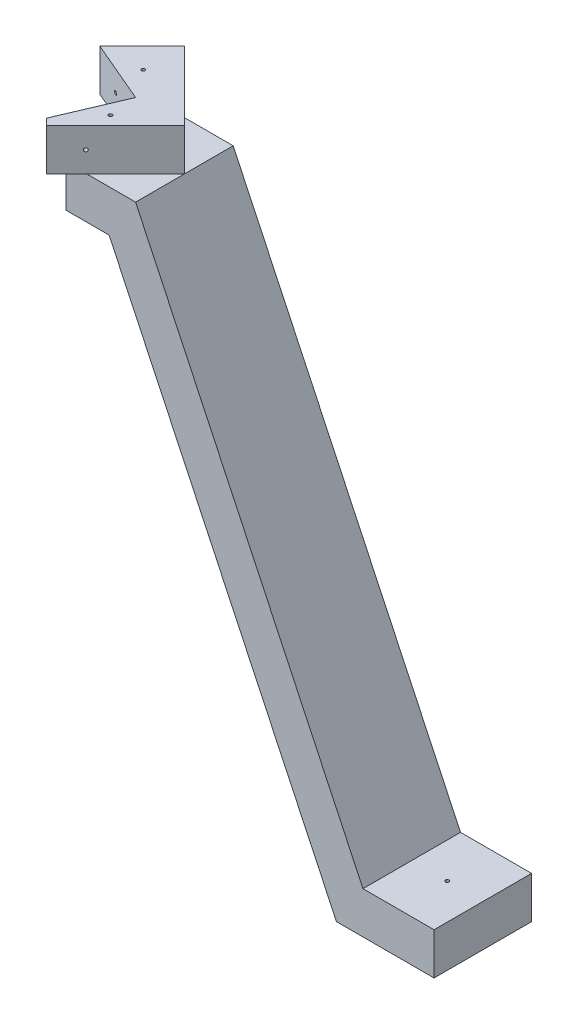
SolidWorks part; units mm, degrees
ref_plane "Frontal Plane" through (0, 0, 0) normal (0, 0, 1) x (1, 0, 0)
ref_plane "Horizontal Plane" through (0, 0, 0) normal (0, 1, 0) x (1, 0, 0)
ref_plane "Profile Plane" through (0, 0, 0) normal (1, 0, 0) x (0, 0, -1)
sketch "Sketch1" plane through (0, 0, 0) normal (0, 0, 1) x (1, 0, 0)
  line L0 (0, 0) -> (-207.1562, 438.15)
  line L2 (-183.0259, 476.25) -> (24.1302, 38.1)
  line L3 (24.1302, 38.1) -> (88.9, 38.1)
  line L4 (88.9, 38.1) -> (88.9, 0)
  line L5 (88.9, 0) -> (0, 0)
  line L6 (-183.0259, 476.25) -> (-271.9259, 476.25)
  line L7 (-271.9259, 476.25) -> (-271.9259, 438.15)
  line L8 (-271.9259, 438.15) -> (-207.1562, 438.15)
  point P7 (-227.4759, 476.25)
  point P9 (56.5151, 38.1)
  dimension "D1" = 38.1
  dimension "D2" = 88.9
  dimension "D3" = 283.991
  dimension "D4" = 438.15
  dimension "D5" = 88.9
  dimension "D6" = 38.1
extrude "Boss-Extrude1" add sketch "Sketch1" along normal mid plane 88.9
hole_wizard "1/8 (0.125) Diameter Hole1" positions "3DSketch1" profile "Sketch3" hole size "1/8" standard "ANSI Inch" end condition through all
sketch3d "3DSketch1"
  line L0 (88.9, 38.1, -44.45) -> (24.1302, 38.1, -44.45) construction
  line L2 (56.5151, 38.1, -44.45) -> (56.5151, 38.1, 44.45) construction
  line L3 (88.9, 38.1, 44.45) -> (24.1302, 38.1, 44.45) construction
  point P0 (56.5151, 38.1, 0)
  dimension "D1" = 44.45
sketch "Sketch3" plane through (56.5151, 38.1, 0) normal (1, 0, 0) x (0, 0, 1)
  line L0 (0, 0) -> (0, 38.1)
  line L1 (0, 38.1) -> (1.5875, 38.1)
  line L2 (1.5875, 38.1) -> (1.5875, 0)
  line L5 (1.5875, 0) -> (0, 0)
  line L11 (0, -6.35) -> (0, 107.95) construction
  dimension "Thru Hole Dia." = 3.175
  dimension "Thru Hole Depth" = 38.1
sketch "Sketch4" plane through (0, 476.25, 0) normal (0, 1, 0) x (1, 0, 0)
  line L0 (-245.8877, 62.8618) -> (-183.0259, 0)
  line L1 (-183.0259, 0) -> (-245.8877, -62.8618)
  line L3 (-245.8877, -62.8618) -> (-308.7495, 0)
  line L4 (-308.7495, 0) -> (-245.8877, 62.8618)
  line L7 (-183.0259, 44.45) -> (-271.9259, 44.45) construction
  line L8 (-271.9259, -44.45) -> (-271.9259, 44.45) construction
  dimension "D1" = 90
  dimension "D3" = 88.9
  dimension "D4" = 44.45
  dimension "D5" = 88.9
extrude "Boss-Extrude2" add sketch "Sketch4" along normal blind 38.1
sketch "Sketch6" plane through (0, 438.15, 0) normal (0, -1, 0) x (1, 0, 0)
  line L0 (-308.7495, 190.3683) -> (-227.4759, 0)
  line L1 (-227.4759, 0) -> (-308.7495, -34.698)
  line L5 (-271.9259, 36.8236) -> (-271.9259, -36.8236) construction
  line L6 (-308.7495, 190.3683) -> (-308.7495, -34.698)
  line L7 (-271.9259, -44.45) -> (-207.1562, -44.45) construction
  line L9 (-227.4759, 0) -> (-342.7269, 0) construction
  dimension "D1" = 44.45
  dimension "D2" = 44.45
  dimension "D3" = 23.119
  dimension "D5" = 66.881
extrude "Cut-Extrude1" cut sketch "Sketch6" against normal through all both and the other way through all
hole_wizard "1/8 (0.125) Diameter Hole2" positions "Sketch7" profile "Sketch8" hole size "1/8" standard "ANSI Inch" end condition through all
sketch "Sketch7" plane through (-91.513, 0, -91.513) normal (0.7071, 0, 0.7071) x (0.7071, 0, -0.7071)
  line L0 (-218.3189, 514.35) -> (-218.3189, 476.25) construction
  line L1 (-218.3189, 476.25) -> (-192.2807, 476.25) construction
  point P0 (-192.9189, 495.3)
  dimension "D1" = 25.4
  dimension "D2" = 19.05
sketch "Sketch8" plane through (-227.9272, 495.3, 44.9013) normal (0, 1, 0) x (0.7071, 0, -0.7071)
  line L0 (0, 0) -> (0, 116.1556)
  line L1 (0, 116.1556) -> (1.5875, 116.1556)
  line L2 (1.5875, 116.1556) -> (1.5875, 0)
  line L5 (1.5875, 0) -> (0, 0)
  line L11 (0, -6.35) -> (0, 107.95) construction
  dimension "Thru Hole Dia." = 3.175
  dimension "Thru Hole Depth" = 116.1556
hole_wizard "1/8 (0.125) Diameter Hole3" positions "Sketch9" profile "Sketch10" hole size "1/8" standard "ANSI Inch" end condition through all
sketch "Sketch9" plane through (-91.513, 0, 91.513) normal (0.7071, 0, -0.7071) x (-0.7071, 0, -0.7071)
  line L0 (218.3189, 514.35) -> (218.3189, 476.25) construction
  line L1 (192.2807, 476.25) -> (218.3189, 476.25) construction
  point P0 (192.9189, 495.3)
  dimension "D1" = 25.4
  dimension "D2" = 19.05
sketch "Sketch10" plane through (-227.9272, 495.3, -44.9013) normal (0, 1, 0) x (-0.7071, 0, -0.7071)
  line L0 (0, 0) -> (0, 116.1556)
  line L1 (0, 116.1556) -> (1.5875, 116.1556)
  line L2 (1.5875, 116.1556) -> (1.5875, 0)
  line L5 (1.5875, 0) -> (0, 0)
  line L11 (0, -6.35) -> (0, 107.95) construction
  dimension "Thru Hole Dia." = 3.175
  dimension "Thru Hole Depth" = 116.1556
hole_wizard "1/8 (0.125) Diameter Hole4" positions "Sketch11" profile "Sketch12" hole size "1/8" standard "ANSI Inch" end condition through all
sketch "Sketch11" plane through (0, 438.15, 0) normal (0, -1, 0) x (-1, 0, 0)
  line L0 (227.4759, -44.45) -> (246.4529, -44.45) construction
  line L2 (271.9259, 44.45) -> (207.1562, 44.45) construction
  line L3 (207.1562, -44.45) -> (207.1562, 44.45) construction
  point P0 (224.9362, -25.4)
  point P2 (245.8877, 25.4)
  dimension "D1" = 19.05
  dimension "D2" = 19.05
  dimension "D4" = 17.78
sketch "Sketch12" plane through (-224.9362, 438.15, 25.4) normal (1, 0, 0) x (0, 0, -1)
  line L0 (0, 0) -> (0, 76.2)
  line L1 (0, 76.2) -> (1.5875, 76.2)
  line L2 (1.5875, 76.2) -> (1.5875, 0)
  line L5 (1.5875, 0) -> (0, 0)
  line L11 (0, -6.35) -> (0, 107.95) construction
  dimension "Thru Hole Dia." = 3.175
  dimension "Thru Hole Depth" = 76.2
